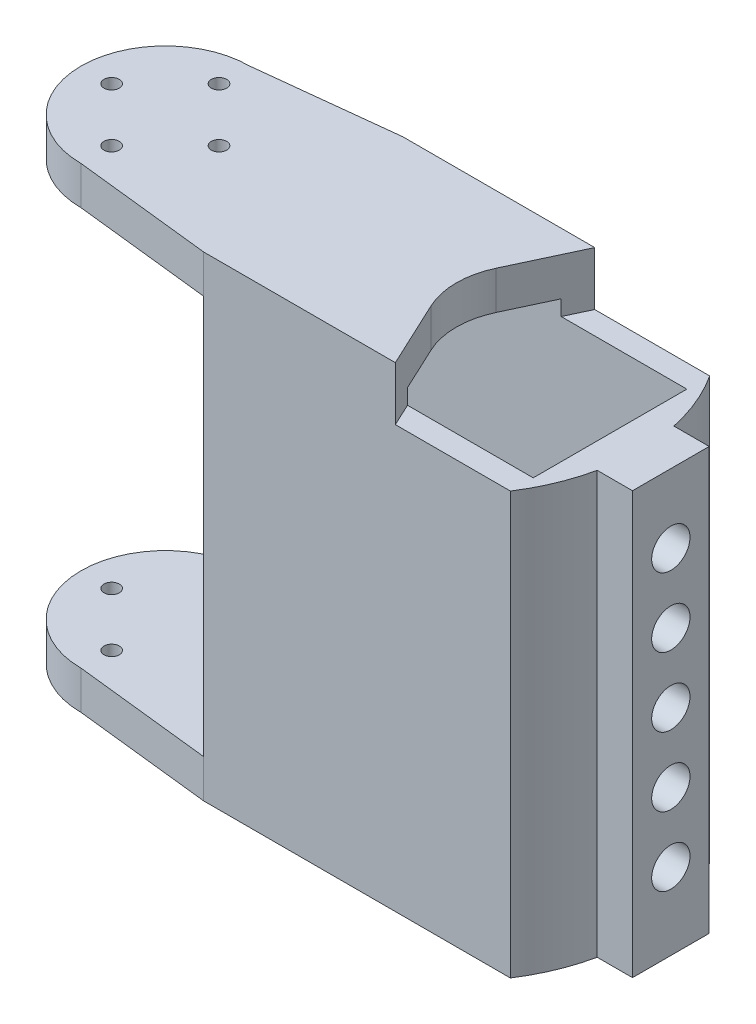
SolidWorks part; units mm, degrees
ref_plane "Front Plane" through (0, 0, 0) normal (0, 0, 1) x (1, 0, 0)
ref_plane "Top Plane" through (0, 0, 0) normal (0, 1, 0) x (1, 0, 0)
ref_plane "Right Plane" through (0, 0, 0) normal (1, 0, 0) x (0, 0, -1)
sketch "Sketch1" plane through (0, 0, 0) normal (0, 1, 0) x (1, 0, 0)
  line L0 (0, 11) -> (18, 13)
  line L1 (0, 0) -> (58.5132, 0) construction
  line L2 (18, 13) -> (58, 13)
  line L3 (58, 10.02) -> (18, 10.02) construction
  line L4 (58, 10.02) -> (58, -10.02) construction
  line L5 (58, -10.02) -> (18, -10.02) construction
  line L6 (18, 10.02) -> (18, -10.02) construction
  line L7 (58, 10.02) -> (18, -10.02) construction
  line L8 (58, -10.02) -> (18, 10.02) construction
  line L9 (0, -11) -> (18, -13)
  line L10 (18, -13) -> (58, -13)
  circle A0 centre (0, 0) radius 11
  circle A1 centre (0, 0) radius 7 construction
  circle A2 centre (0, 7) radius 1
  circle A3 centre (7, 0) radius 1
  circle A4 centre (0, -7) radius 1
  circle A5 centre (-7, 0) radius 1
  arc A7 (58, -13) -> (58, 13) centre (38, 0) ccw
  point P8 (38, 0)
  point P15 (0, 0)
  point P22 (0, 0)
  point P25 (31, 0)
  point P28 (0, 0)
  point P29 (0, 0)
  dimension "D1" = 22
  dimension "D2" = 14
  dimension "D4" = 2
  dimension "D5" = 40
  dimension "D6" = 20.04
  dimension "D7" = 18
  dimension "D8" = 2
  dimension "D3" = 4
extrude "Boss-Extrude1" add sketch "Sketch1" along normal blind 62 contours L10 A7 L2 L0 A0 L9 | A0 A5 A4 A3 A2
sketch "Sketch2" plane through (0, 0, 0) normal (0, 0, 1) x (1, 0, 0)
  line L0 (-11, 62) -> (-11, 0) construction
  line L1 (-11, 57) -> (58, 57)
  line L2 (-11, 57) -> (-11, 5)
  line L3 (-11, 5) -> (58, 5)
  line L4 (58, 57) -> (58, 5)
  line L5 (0, 62) -> (-11, 62) construction
  line L6 (58, 62) -> (58, 0) construction
  dimension "D1" = 52
  dimension "D2" = 5
extrude "Cut-Extrude1" cut sketch "Sketch2" against normal mid plane 20.04
sketch "Sketch4" plane through (0, 0, 0) normal (0, 0, 1) x (1, 0, 0)
  line L1 (-4.5387, 57) -> (18, 57)
  line L2 (-4.5387, 57) -> (-4.5387, 5)
  line L3 (-4.5387, 5) -> (18, 5)
  line L4 (18, 57) -> (18, 5)
  line L5 (18, 62) -> (18, 0) construction
  point P7 (0, 0)
  point P9 (0, 0)
extrude "Cut-Extrude2" cut sketch "Sketch4" against normal mid plane 72.04
sketch "Sketch5" plane through (0, 62, 0) normal (0, 1, 0) x (1, 0, 0)
  line L0 (0, 0) -> (58.5132, 0) construction
  line L1 (58, 10.02) -> (58, -10.02) construction
  line L2 (58, 10.02) -> (18, 10.02) construction
  line L3 (18, -13) -> (58, -13) construction
  line L4 (18, 13) -> (58, 13) construction
  line L5 (43, -13) -> (58, -13)
  line L6 (43, 13) -> (58, 13)
  line L7 (43, 13) -> (38.9043, 4.2464)
  line L9 (38.9043, -4.2464) -> (43, -13)
  arc A0 (38.9043, 4.2464) -> (38.9043, -4.2464) centre (47.98, 0) ccw
  arc A1 (58, -13) -> (58, 13) centre (38, 0) ccw construction
  arc A2 (58, -13) -> (58, 13) centre (38, 0) ccw
  point P15 (0, 0)
  dimension "D1" = 15
  dimension "D2" = 15
extrude "Cut-Extrude3" cut sketch "Sketch5" against normal blind 7
sketch "Sketch6" plane through (0, 0, 0) normal (0, -1, 0) x (1, 0, 0)
  circle A0 centre (47.98, 0) radius 10.02
  point P7 (42.3467, -8.2865)
  point P10 (0, 0)
  dimension "D2" = 20.04
extrude "Cut-Extrude6" cut sketch "Sketch6" against normal up to surface (5 mm away) up to face at (22.125, 5, 0)
sketch "Sketch10" plane through (0, 0, 13) normal (0, 0, 1) x (1, 0, 0)
  line L0 (61.8537, 55) -> (58, 55) construction
  line L1 (59.9269, 55) -> (65.9269, 55)
  line L2 (59.9269, 55) -> (59.9269, 0)
  line L3 (59.9269, 0) -> (65.9269, 0)
  line L4 (65.9269, 55) -> (65.9269, 0)
  line L5 (18, 0) -> (58, 0) construction
  dimension "D1" = 6
extrude "Boss-Extrude3" add sketch "Sketch10" along normal mid plane 10 from surface at -13 starting at plane "Front Plane"
sketch "Sketch11" plane through (65.9269, 0, 0) normal (1, 0, 0) x (0, 0, -1)
  line L0 (0, 0) -> (0, 55) construction
  line L1 (-5, 55) -> (5, 55) construction
  circle A0 centre (0, 46) radius 2.5
  circle A1 centre (0, 37) radius 2.5
  circle A2 centre (0, 28) radius 2.5
  circle A3 centre (0, 19) radius 2.5
  circle A4 centre (0, 10) radius 2.5
  dimension "D1" = 5
  dimension "D2" = 9
  dimension "D3" = 5
extrude "Cut-Extrude7" cut sketch "Sketch11" against normal blind 5
